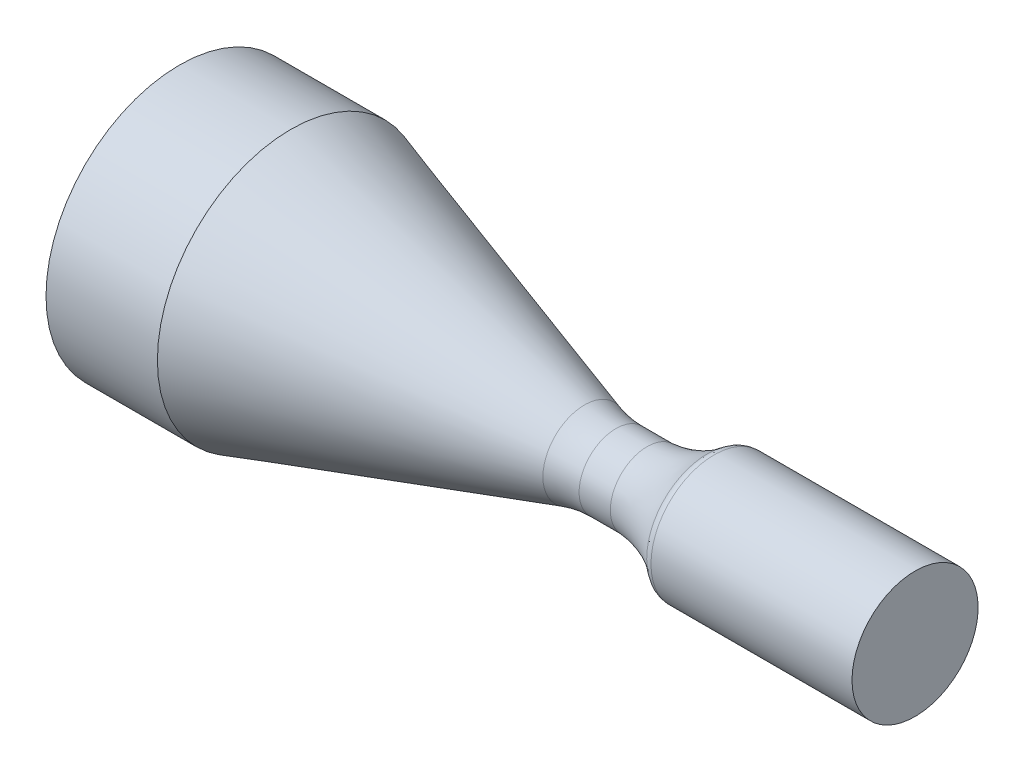
SolidWorks part; units mm, degrees
ref_plane "Front Plane" through (0, 0, 0) normal (0, 0, 1) x (1, 0, 0)
ref_plane "Top Plane" through (0, 0, 0) normal (0, 1, 0) x (1, 0, 0)
ref_plane "Right Plane" through (0, 0, 0) normal (1, 0, 0) x (0, 0, -1)
sketch "Sketch1" plane through (0, 0, 0) normal (0, 1, 0) x (1, 0, 0)
  line L0 (0, 0) -> (5630.0574, 0) construction
  line L16 (200, 0) -> (200, 127)
  line L17 (200, 127) -> (306, 127)
  line L18 (306, 127) -> (585.4164, 39.5636)
  line L19 (615.2809, 35) -> (645, 35)
  line L21 (708.6944, 60) -> (900, 60)
  line L22 (900, 60) -> (900, 0)
  line L23 (900, 0) -> (200, 0)
  arc A0 (645, 35) -> (702.3246, 57.7088) centre (638.6264, 134.7967) ccw
  arc A1 (708.6944, 60) -> (702.3246, 57.7088) centre (708.6944, 50) ccw
  arc A2 (615.2809, 35) -> (585.4164, 39.5636) centre (615.2809, 135) cw
  point P15 (705, 60)
  dimension "D9" = 35
  dimension "D10" = 10
  dimension "D6" = 100
  dimension "D3" = 100
  dimension "D1" = 200
  dimension "D2" = 106
  dimension "D4" = 60
  dimension "D5" = 127
  dimension "D7" = 700
  dimension "D8" = 505
revolve "Revolve1" add sketch "Sketch1" angle 360 about L0
ref_plane "Plane1" through (305, 0, 0) normal (1, 0, 0) x (0, 0, -1)
ref_plane "Plane2" through (709, 0, 0) normal (1, 0, 0) x (0, 0, -1)
ref_plane "Plane3" through (638, 0, 0) normal (-1, 0, 0) x (0, 0, 1)
